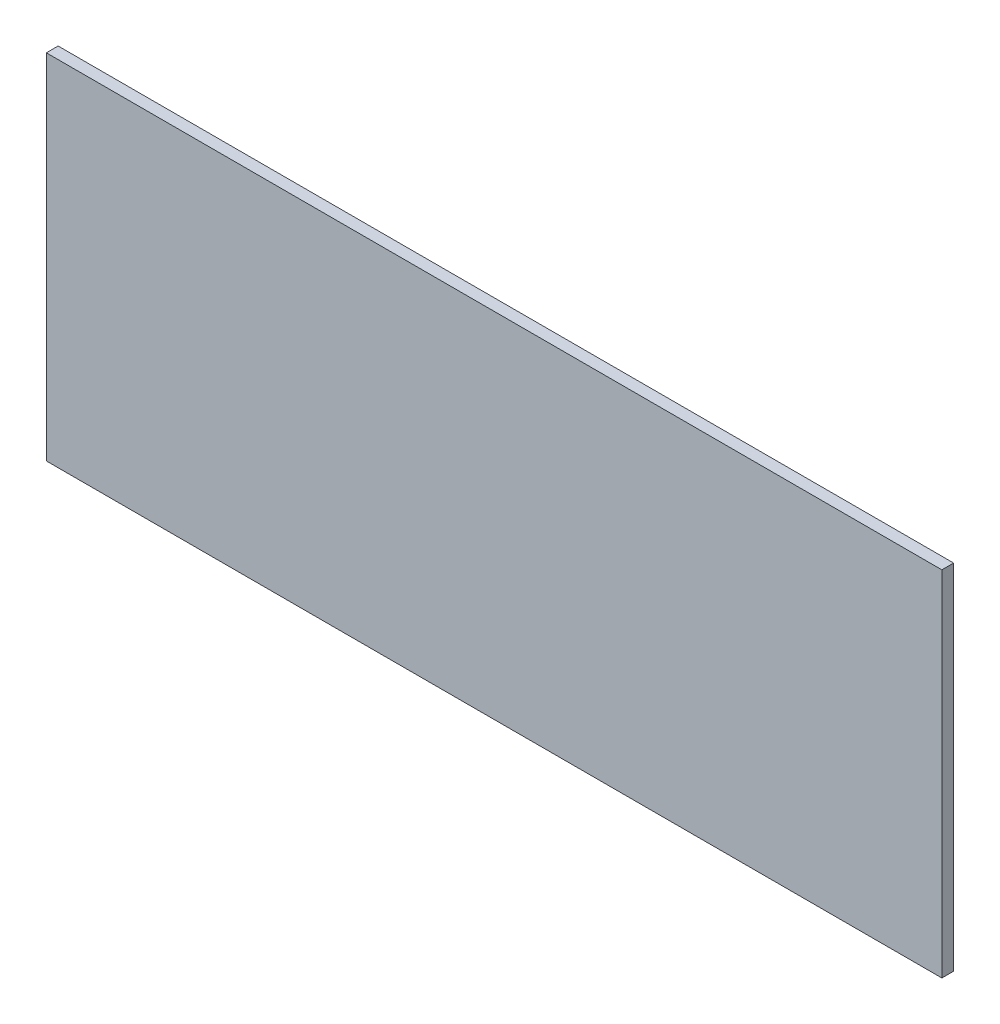
SolidWorks part; units mm, degrees
ref_plane "Plan de face" through (0, 0, 0) normal (0, 0, 1) x (1, 0, 0)
ref_plane "Plan de dessus" through (0, 0, 0) normal (0, 1, 0) x (1, 0, 0)
ref_plane "Plan de droite" through (0, 0, 0) normal (1, 0, 0) x (0, 0, -1)
sketch "Esquisse1" plane through (0, 0, 0) normal (0, 0, 1) x (1, 0, 0)
  line L1 (-191.5313, 22.8927) -> (188.4687, 22.8927)
  line L2 (-191.5313, 22.8927) -> (-191.5313, -127.1073)
  line L3 (-191.5313, -127.1073) -> (188.4687, -127.1073)
  line L4 (188.4687, 22.8927) -> (188.4687, -127.1073)
  dimension "D1" = 380
  dimension "D2" = 150
extrude "Boss.-Extru.1" add sketch "Esquisse1" along normal blind 5
